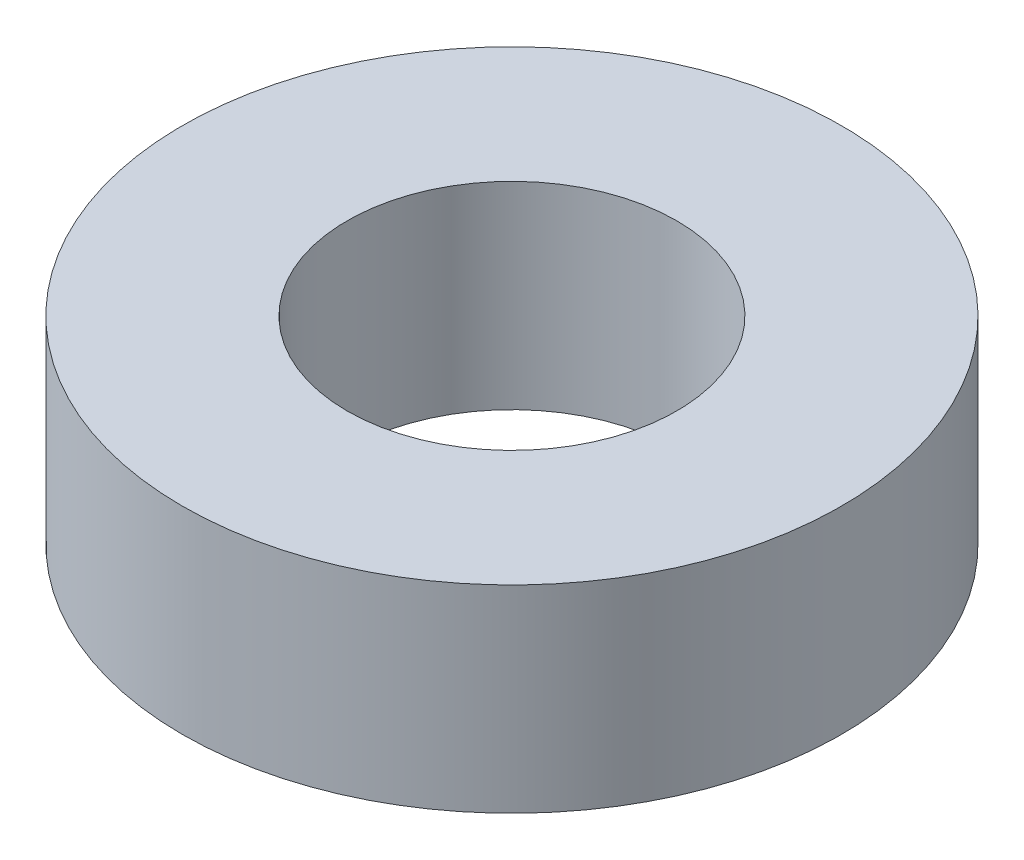
SolidWorks part; units mm, degrees
ref_plane "Front Plane" through (0, 0, 0) normal (0, 0, 1) x (1, 0, 0)
ref_plane "Top Plane" through (0, 0, 0) normal (0, 1, 0) x (1, 0, 0)
ref_plane "Right Plane" through (0, 0, 0) normal (1, 0, 0) x (0, 0, -1)
sketch "Sketch1" plane through (0, 0, 0) normal (0, 1, 0) x (1, 0, 0)
  circle A0 centre (0, 0) radius 5
  circle A1 centre (0, 0) radius 2.5
  dimension "D1" = 5
  dimension "D2" = 10
extrude "Boss-Extrude1" add sketch "Sketch1" along normal blind 3
